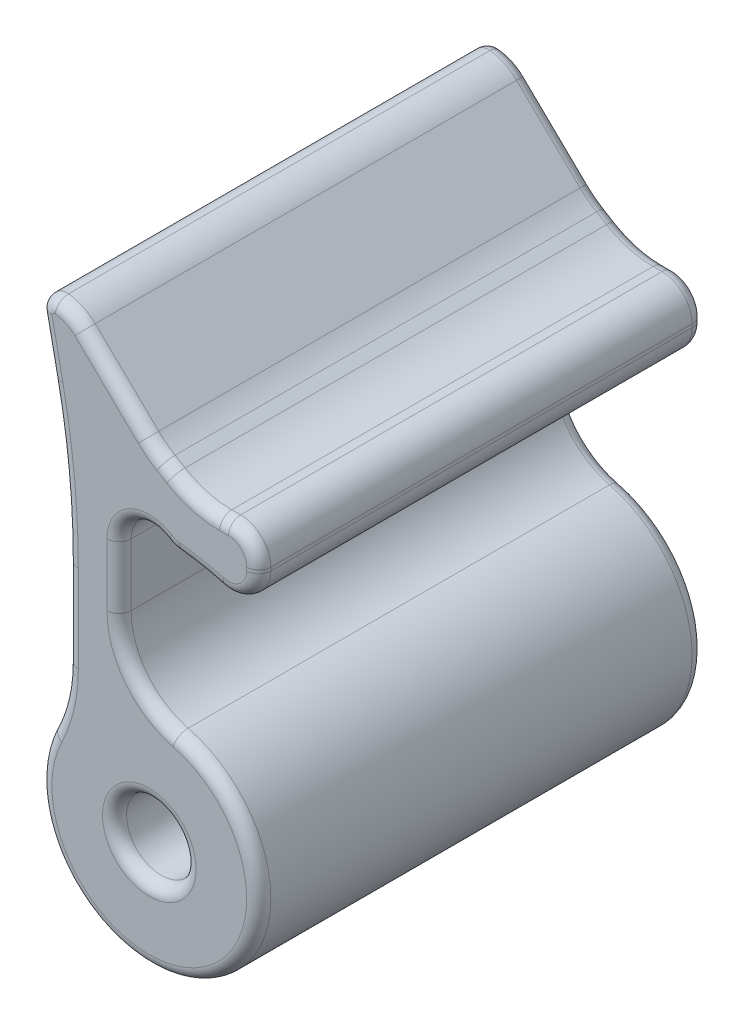
SolidWorks part; units mm, degrees
ref_plane "前视基准面" through (0, 0, 0) normal (0, 0, 1) x (1, 0, 0)
ref_plane "上视基准面" through (0, 0, 0) normal (0, 1, 0) x (1, 0, 0)
ref_plane "右视基准面" through (0, 0, 0) normal (1, 0, 0) x (0, 0, -1)
sketch "草图1" plane through (0, 0, 0) normal (0, 0, 1) x (1, 0, 0)
  line L1 (49.8411, 44.8171) -> (48.0552, 44.8171)
  line L5 (51.8411, 46.8171) -> (51.8411, 47.8171)
  line L12 (45.5041, 51.0693) -> (46.166, 50.6721)
  line L13 (49.8411, 49.8171) -> (49.253, 49.8171)
  line L22 (42.5911, 56.8171) -> (42.5911, 56.2142)
  line L23 (37.3411, 44.8171) -> (37.3411, 56.8171)
  line L24 (37.3411, 56.8171) -> (42.5911, 56.8171)
  line L25 (42.5911, 44.8171) -> (42.5911, 40.6941)
  line L26 (37.3411, 44.8171) -> (37.3411, 28.8171)
  circle A0 centre (44.5911, 28.8171) radius 2.3
  arc A1 (37.3411, 28.8171) -> (46.3666, 35.8463) centre (44.5911, 28.8171) ccw
  arc A2 (46.3232, 45.8171) -> (42.5911, 44.8171) centre (44.5911, 44.8171) ccw
  arc A6 (49.8411, 44.8171) -> (51.8411, 46.8171) centre (49.8411, 46.8171) ccw
  arc A7 (51.8411, 47.8171) -> (49.8411, 49.8171) centre (49.8411, 47.8171) ccw
  arc A8 (46.3232, 45.8171) -> (48.0552, 44.8171) centre (48.0552, 46.8171) ccw
  arc A9 (42.5911, 40.6941) -> (46.3666, 35.8463) centre (47.5911, 40.6941) ccw
  arc A11 (49.253, 49.8171) -> (46.166, 50.6721) centre (49.253, 55.8171) cw
  arc A12 (42.5911, 56.2142) -> (45.5041, 51.0693) centre (48.5911, 56.2142) ccw
  point P20 (51.8411, 44.8171)
  dimension "D1" = 6
  dimension "D3" = 2
  dimension "D4" = 2
  dimension "D5" = 5
extrude "凸台-拉伸1" add sketch "草图1" along normal blind 29.5
sketch "草图3" plane through (0, 0, 29.5) normal (0, 0, 1) x (1, 0, 0)
  line L1 (42.5911, 56.8171) -> (37.3411, 56.8171) construction
  line L2 (39.3411, 56.8171) -> (44.4182, 51.903)
  line L3 (42.5911, 56.2142) -> (42.5911, 56.8171)
  line L4 (42.5911, 56.8171) -> (39.3411, 56.8171)
  arc A0 (42.5911, 56.2142) -> (45.5041, 51.0693) centre (48.5911, 56.2142) ccw construction
  arc A1 (42.5911, 56.2142) -> (44.4182, 51.903) centre (48.5911, 56.2142) ccw
extrude "切除-拉伸2" cut sketch "草图3" against normal through all
fillet "圆角4" radius 3 1 edges at (39.3411, 56.8171, 14.75)
fillet "圆角5" radius 1 1 edges at (37.3411, 56.8171, 14.75)
sketch "草图4" plane through (0, 0, 29.5) normal (0, 0, 1) x (1, 0, 0)
  line L0 (48.0552, 44.8171) -> (49.8411, 44.8171) construction
  line L1 (48.0552, 44.8171) -> (49.8411, 44.8171)
  arc A0 (50.9195, 45.1328) -> (45.9735, 46.2624) centre (44.5911, 28.8171) ccw
  arc A1 (49.8411, 44.8171) -> (51.8411, 46.8171) centre (49.8411, 46.8171) ccw construction
  arc A2 (46.3232, 45.8171) -> (42.5911, 44.8171) centre (44.5911, 44.8171) ccw construction
  arc A3 (46.3232, 45.8171) -> (48.0552, 44.8171) centre (48.0552, 46.8171) ccw construction
  arc A4 (49.8411, 44.8171) -> (50.9195, 45.1328) centre (49.8411, 46.8171) ccw
  arc A5 (46.3232, 45.8171) -> (45.9735, 46.2624) centre (44.5911, 44.8171) ccw
  arc A6 (46.3232, 45.8171) -> (48.0552, 44.8171) centre (48.0552, 46.8171) ccw
extrude "切除-拉伸3" cut sketch "草图4" against normal through all
sketch "草图5" plane through (0, 0, 29.5) normal (0, 0, 1) x (1, 0, 0)
  line L2 (39.0911, 40.6941) -> (39.0911, 36.3876)
  line L5 (39.0911, 40.6941) -> (39.0911, 42.1784)
  line L6 (37.3411, 55.8056) -> (38.0825, 52.1705)
  line L7 (37.3411, 55.8056) -> (37.3411, 28.8171)
  arc A0 (38.0766, 31.9989) -> (37.3411, 28.8171) centre (44.5911, 28.8171) ccw
  arc A1 (39.0911, 36.3876) -> (38.0766, 31.9989) centre (29.0911, 36.3876) cw
  arc A2 (38.0825, 52.1705) -> (39.0911, 42.1784) centre (-10.9089, 42.1784) cw
  dimension "D1" = 10
  dimension "D2" = 50
extrude "切除-拉伸4" cut sketch "草图5" against normal through all
fillet "圆角6" radius 2 2 edges at (45.9735, 46.2624, 14.75) (50.9195, 45.1328, 14.75)
fillet "圆角7" radius 0.8 42 edges at (46.8911, 28.8171, 0) (51.05, 46.0038, 0) (51.8411, 47.7071, 0) (51.2553, 49.2313, 0) (49.5471, 49.8171, 0) (47.6514, 50.0348, 0) (45.8351, 50.8707, 0) (44.9373, 51.455, 0) (42.3159, 53.9378, 0) (39.3999, 56.5337, 0) (37.6729, 56.5496, 0) (47.6432, 22.2408, 0) (43.6463, 37.6218, 0) (42.5911, 42.7556, 0) (43.6253, 46.5685, 0) (46.0657, 46.3119, 0) (47.9157, 45.9984, 0) (46.8911, 28.8171, 29.5) (42.5911, 42.7556, 29.5) (43.6463, 37.6218, 29.5) (47.6432, 22.2408, 29.5) (37.6729, 56.5496, 29.5) (39.3999, 56.5337, 29.5) (42.3159, 53.9378, 29.5) (44.9373, 51.455, 29.5) (45.8351, 50.8707, 29.5) (47.6514, 50.0348, 29.5) (49.5471, 49.8171, 29.5) (51.2553, 49.2313, 29.5) (51.8411, 47.7071, 29.5) (51.05, 46.0038, 29.5) (47.9157, 45.9984, 29.5) (46.0657, 46.3119, 29.5) (43.6253, 46.5685, 29.5) (37.7118, 53.988, 0) (38.8383, 47.1998, 0) (39.0911, 39.283, 0) (38.8342, 34.1354, 0) (38.8342, 34.1354, 29.5) (39.0911, 39.283, 29.5) (38.8383, 47.1998, 29.5) (37.7118, 53.988, 29.5)
